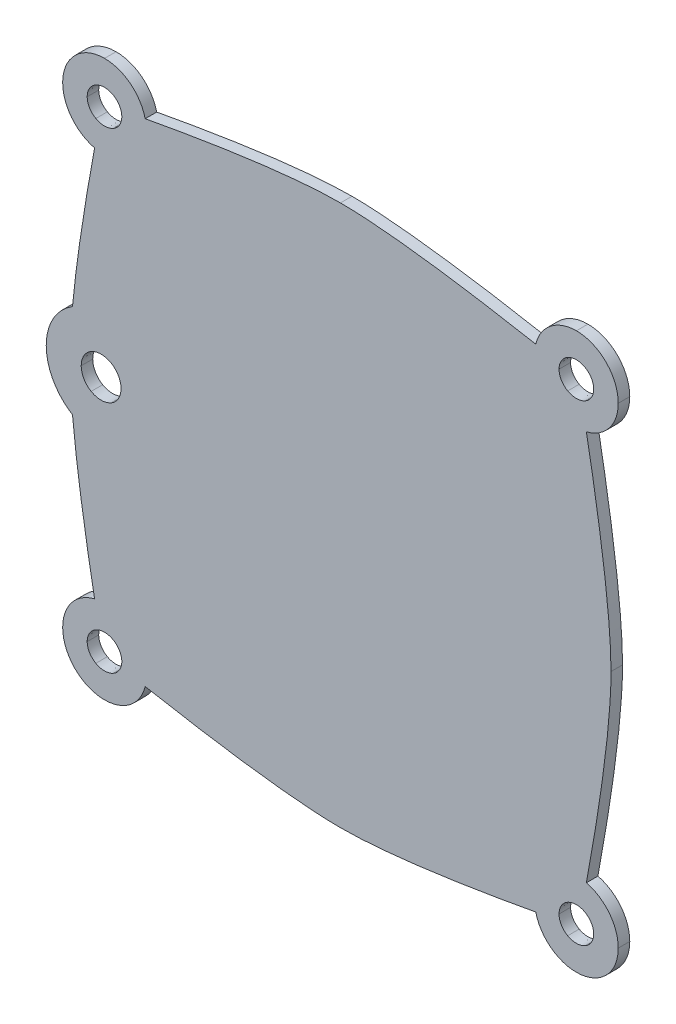
SolidWorks part; units mm, degrees
ref_plane "Front Plane" through (0, 0, 0) normal (0, 0, 1) x (1, 0, 0)
ref_plane "Top Plane" through (0, 0, 0) normal (0, 1, 0) x (1, 0, 0)
ref_plane "Right Plane" through (0, 0, 0) normal (1, 0, 0) x (0, 0, -1)
sketch "Model" plane through (0, 0, 0) normal (0, 0, 1) x (1, 0, 0)
  spline S120 degree 3 poles (89.6795, 301.3132) (86.4943, 301.3132) (83.9116, 298.7305) (83.9116, 295.5453) knots 0 0 0 0 1 1 1 1
  spline S121 degree 3 poles (83.9116, 295.5453) (83.9116, 292.8299) (85.7855, 290.5577) (88.3125, 289.9449) knots 0 0 0 0 1 1 1 1
  spline S122 degree 3 poles (88.3125, 289.9449) (87.3105, 284.566) (85.9084, 276.3884) (85.261, 269.4838) knots 0 0 0 0 1 1 1 1
  spline S123 degree 3 poles (85.261, 269.4838) (83.0934, 268.1544) (81.645, 265.766) (81.645, 263.0368) knots 0 0 0 0 1 1 1 1
  spline S124 degree 3 poles (81.645, 263.0368) (81.645, 260.3077) (83.0934, 257.9104) (85.261, 256.581) knots 0 0 0 0 1 1 1 1
  spline S125 degree 3 poles (85.261, 256.581) (85.906, 249.6777) (87.3023, 241.5092) (88.3037, 236.1287) knots 0 0 0 0 1 1 1 1
  spline S126 degree 3 poles (88.3037, 236.1287) (85.7806, 235.5132) (83.9116, 233.2409) (83.9116, 230.5283) knots 0 0 0 0 1 1 1 1
  spline S127 degree 3 poles (83.9116, 230.5283) (83.9116, 227.3431) (86.4943, 224.7604) (89.6795, 224.7604) knots 0 0 0 0 1 1 1 1
  spline S128 degree 3 poles (89.6795, 224.7604) (92.3921, 224.7604) (94.6644, 226.6295) (95.2799, 229.1525) knots 0 0 0 0 1 1 1 1
  spline S129 degree 3 poles (95.2799, 229.1525) (102.4919, 227.8103) (114.7298, 225.757) (122.188, 225.757) knots 0 0 0 0 1 1 1 1
  spline S130 degree 3 poles (122.188, 225.757) (129.6462, 225.757) (141.884, 227.8103) (149.0961, 229.1525) knots 0 0 0 0 1 1 1 1
  spline S131 degree 3 poles (149.0961, 229.1525) (149.7118, 226.6297) (151.984, 224.7604) (154.6964, 224.7604) knots 0 0 0 0 1 1 1 1
  spline S132 degree 3 poles (154.6964, 224.7604) (157.8817, 224.7604) (160.4644, 227.3431) (160.4644, 230.5283) knots 0 0 0 0 1 1 1 1
  spline S133 degree 3 poles (160.4644, 230.5283) (160.4644, 233.2386) (158.5921, 235.5109) (156.0723, 236.1287) knots 0 0 0 0 1 1 1 1
  spline S134 degree 3 poles (156.0723, 236.1287) (157.4145, 243.3408) (159.4678, 255.5786) (159.4678, 263.0368) knots 0 0 0 0 1 1 1 1
  spline S135 degree 3 poles (159.4678, 263.0368) (159.4678, 270.495) (157.4145, 282.7329) (156.0723, 289.9449) knots 0 0 0 0 1 1 1 1
  spline S136 degree 3 poles (156.0723, 289.9449) (158.5919, 290.5628) (160.4644, 292.8351) (160.4644, 295.5453) knots 0 0 0 0 1 1 1 1
  spline S137 degree 3 poles (160.4644, 295.5453) (160.4644, 298.7305) (157.8817, 301.3132) (154.6964, 301.3132) knots 0 0 0 0 1 1 1 1
  spline S138 degree 3 poles (154.6964, 301.3132) (151.9863, 301.3132) (149.714, 299.4408) (149.0961, 296.9211) knots 0 0 0 0 1 1 1 1
  spline S139 degree 3 poles (149.0961, 296.9211) (141.884, 298.2633) (129.6462, 300.3166) (122.188, 300.3166) knots 0 0 0 0 1 1 1 1
  spline S140 degree 3 poles (122.188, 300.3166) (114.7283, 300.3166) (102.4906, 298.2554) (95.2799, 296.9123) knots 0 0 0 0 1 1 1 1
  spline S141 degree 3 poles (95.2799, 296.9123) (94.6651, 299.4364) (92.3929, 301.3132) (89.6795, 301.3132) knots 0 0 0 0 1 1 1 1
  spline S142 degree 3 poles (92.0595, 295.542) (92.0595, 294.7171) (91.6047, 293.9549) (90.8666, 293.5425) knots 0 0 0 0 1 1 1 1
  spline S143 degree 3 poles (90.8666, 293.5425) (90.1284, 293.1301) (89.2189, 293.1301) (88.4808, 293.5425) knots 0 0 0 0 1 1 1 1
  spline S144 degree 3 poles (88.4808, 293.5425) (87.7426, 293.9549) (87.2879, 294.7171) (87.2879, 295.542) knots 0 0 0 0 1 1 1 1
  spline S145 degree 3 poles (87.2879, 295.542) (87.2879, 296.3668) (87.7426, 297.129) (88.4808, 297.5414) knots 0 0 0 0 1 1 1 1
  spline S146 degree 3 poles (88.4808, 297.5414) (89.2189, 297.9538) (90.1284, 297.9538) (90.8666, 297.5414) knots 0 0 0 0 1 1 1 1
  spline S147 degree 3 poles (90.8666, 297.5414) (91.6047, 297.129) (92.0595, 296.3668) (92.0595, 295.542) knots 0 0 0 0 1 1 1 1
  spline S148 degree 3 poles (157.078, 230.5234) (157.078, 229.6986) (156.6233, 228.9364) (155.8851, 228.524) knots 0 0 0 0 1 1 1 1
  spline S149 degree 3 poles (155.8851, 228.524) (155.1469, 228.1116) (154.2375, 228.1116) (153.4993, 228.524) knots 0 0 0 0 1 1 1 1
  spline S150 degree 3 poles (153.4993, 228.524) (152.7611, 228.9364) (152.3064, 229.6986) (152.3064, 230.5234) knots 0 0 0 0 1 1 1 1
  spline S151 degree 3 poles (152.3064, 230.5234) (152.3064, 231.3483) (152.7611, 232.1105) (153.4993, 232.5229) knots 0 0 0 0 1 1 1 1
  spline S152 degree 3 poles (153.4993, 232.5229) (154.2375, 232.9353) (155.1469, 232.9353) (155.8851, 232.5229) knots 0 0 0 0 1 1 1 1
  spline S153 degree 3 poles (155.8851, 232.5229) (156.6233, 232.1105) (157.078, 231.3483) (157.078, 230.5234) knots 0 0 0 0 1 1 1 1
  spline S154 degree 3 poles (92.0595, 230.5234) (92.0595, 229.6986) (91.6047, 228.9364) (90.8666, 228.524) knots 0 0 0 0 1 1 1 1
  spline S155 degree 3 poles (90.8666, 228.524) (90.1284, 228.1116) (89.2189, 228.1116) (88.4808, 228.524) knots 0 0 0 0 1 1 1 1
  spline S156 degree 3 poles (88.4808, 228.524) (87.7426, 228.9364) (87.2879, 229.6986) (87.2879, 230.5234) knots 0 0 0 0 1 1 1 1
  spline S157 degree 3 poles (87.2879, 230.5234) (87.2879, 231.3483) (87.7426, 232.1105) (88.4808, 232.5229) knots 0 0 0 0 1 1 1 1
  spline S158 degree 3 poles (88.4808, 232.5229) (89.2189, 232.9353) (90.1284, 232.9353) (90.8666, 232.5229) knots 0 0 0 0 1 1 1 1
  spline S159 degree 3 poles (90.8666, 232.5229) (91.6047, 232.1105) (92.0595, 231.3483) (92.0595, 230.5234) knots 0 0 0 0 1 1 1 1
  spline S160 degree 3 poles (157.078, 295.542) (157.078, 294.7171) (156.6233, 293.9549) (155.8851, 293.5425) knots 0 0 0 0 1 1 1 1
  spline S161 degree 3 poles (155.8851, 293.5425) (155.1469, 293.1301) (154.2375, 293.1301) (153.4993, 293.5425) knots 0 0 0 0 1 1 1 1
  spline S162 degree 3 poles (153.4993, 293.5425) (152.7611, 293.9549) (152.3064, 294.7171) (152.3064, 295.542) knots 0 0 0 0 1 1 1 1
  spline S163 degree 3 poles (152.3064, 295.542) (152.3064, 296.3668) (152.7611, 297.129) (153.4993, 297.5414) knots 0 0 0 0 1 1 1 1
  spline S164 degree 3 poles (153.4993, 297.5414) (154.2375, 297.9538) (155.1469, 297.9538) (155.8851, 297.5414) knots 0 0 0 0 1 1 1 1
  spline S165 degree 3 poles (155.8851, 297.5414) (156.6233, 297.129) (157.078, 296.3668) (157.078, 295.542) knots 0 0 0 0 1 1 1 1
  spline S166 degree 3 poles (91.9523, 263.0327) (91.953, 262.052) (91.4302, 261.1456) (90.581, 260.6551) knots 0 0 0 0 1 1 1 1
  spline S167 degree 3 poles (90.581, 260.6551) (89.7318, 260.1645) (88.6854, 260.1645) (87.8363, 260.6551) knots 0 0 0 0 1 1 1 1
  spline S168 degree 3 poles (87.8363, 260.6551) (86.9871, 261.1456) (86.4643, 262.052) (86.4649, 263.0327) knots 0 0 0 0 1 1 1 1
  spline S169 degree 3 poles (86.4649, 263.0327) (86.4643, 264.0134) (86.9871, 264.9198) (87.8363, 265.4104) knots 0 0 0 0 1 1 1 1
  spline S170 degree 3 poles (87.8363, 265.4104) (88.6854, 265.9009) (89.7318, 265.9009) (90.581, 265.4104) knots 0 0 0 0 1 1 1 1
  spline S171 degree 3 poles (90.581, 265.4104) (91.4302, 264.9198) (91.953, 264.0134) (91.9523, 263.0327) knots 0 0 0 0 1 1 1 1
extrude "Boss-Extrude1" add sketch "Model" along normal blind 1.5875 contours S125 S126 S127 S128 S129 S130 S131 S132 S133 S134 S135 S136 S137 S138 S139 S140 S141 S120 S121 S122 S123 S124 | S167 S168 S169 S170 S171 S166 | S143 S144 S145 S146 S147 S142 | S161 S162 S163 S164 S165 S160 | S149 S150 S151 S152 S153 S148 | S155 S156 S157 S158 S159 S154
